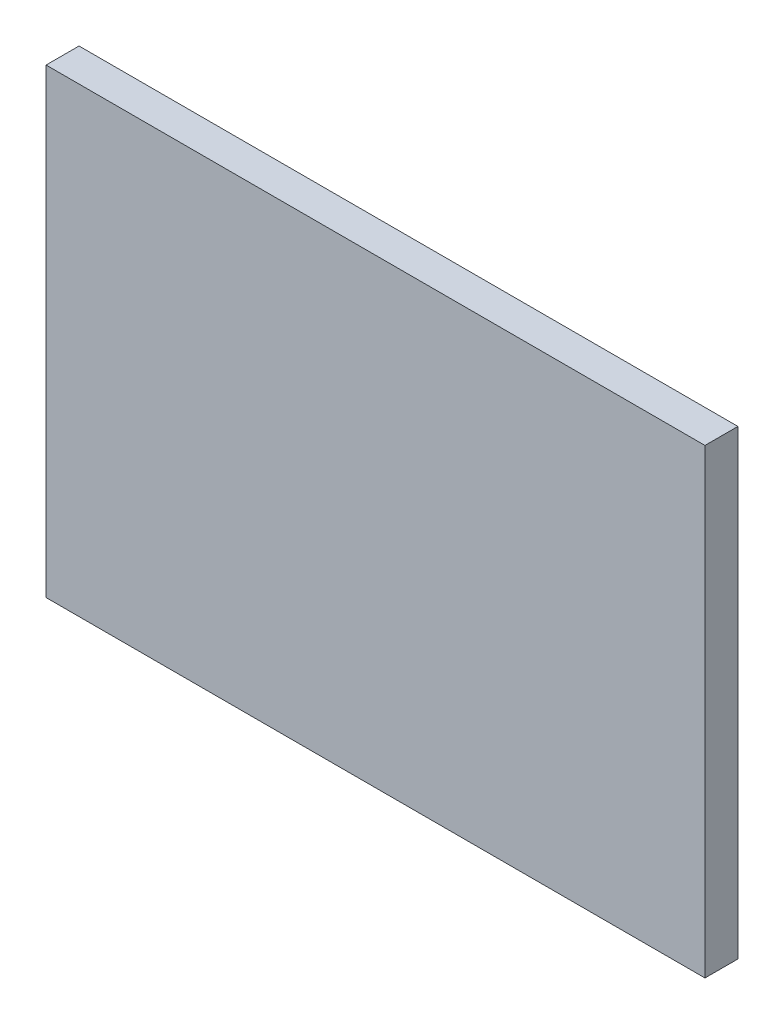
SolidWorks part; units mm, degrees
material "бетон"
ref_plane "Front Plane" through (0, 0, 0) normal (0, 0, 1) x (1, 0, 0)
ref_plane "Top Plane" through (0, 0, 0) normal (0, 1, 0) x (1, 0, 0)
ref_plane "Right Plane" through (0, 0, 0) normal (1, 0, 0) x (0, 0, -1)
sketch "Эскиз1" plane through (0, 0, 0) normal (0, 1, 0) x (1, 0, 0)
  line L1 (0, 0) -> (200, 0)
  line L2 (0, 0) -> (0, 10)
  line L3 (0, 10) -> (200, 10)
  line L4 (200, 0) -> (200, 10)
extrude "Бобышка-Вытянуть1" add sketch "Эскиз1" against normal blind 140
